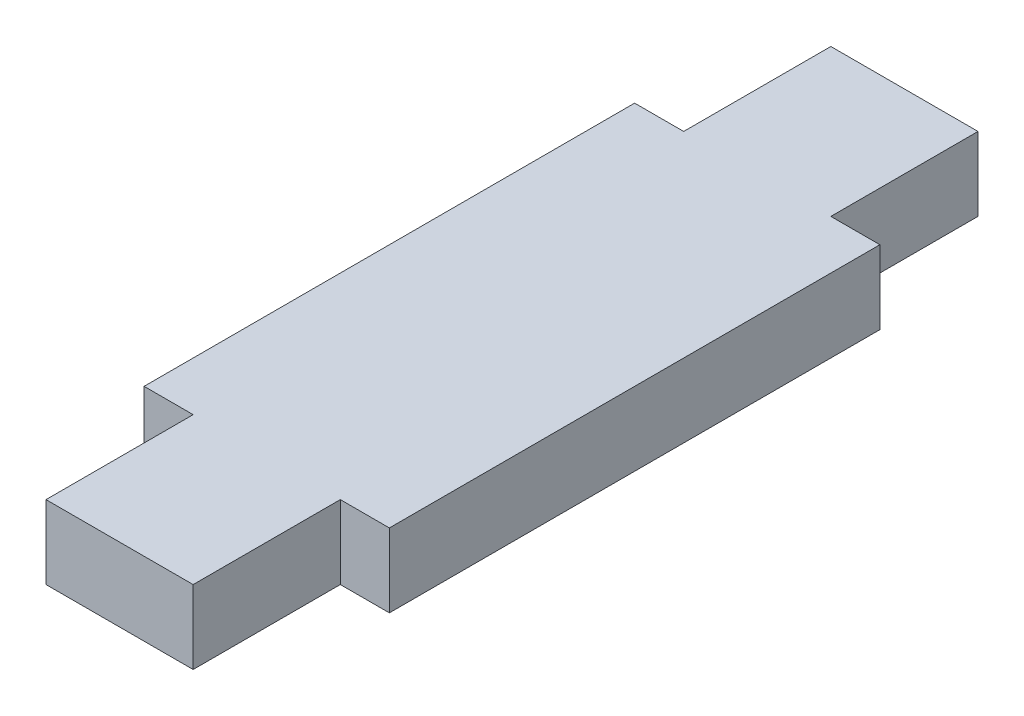
SolidWorks part; units mm, degrees
ref_plane "Front Plane" through (0, 0, 0) normal (0, 0, 1) x (1, 0, 0)
ref_plane "Top Plane" through (0, 0, 0) normal (0, 1, 0) x (1, 0, 0)
ref_plane "Right Plane" through (0, 0, 0) normal (1, 0, 0) x (0, 0, -1)
other "Configuration Table"
sketch "Sketch1" plane through (0, 0, 0) normal (0, 1, 0) x (1, 0, 0)
  line L0 (-5, 10) -> (-3, 10)
  line L2 (-5, 10) -> (-5, -10)
  line L4 (5, 10) -> (5, -10)
  line L5 (-5, 10) -> (5, -10) construction
  line L6 (-5, -10) -> (5, 10) construction
  line L12 (-3, 10) -> (-3, 16)
  line L17 (-3, 16) -> (3, 16)
  line L18 (3, 10) -> (3, 16)
  line L19 (3, 10) -> (5, 10)
  line L20 (-5, 0) -> (5, 0) construction
  line L21 (3, -10) -> (5, -10)
  line L22 (3, -10) -> (3, -16)
  line L23 (-3, -16) -> (3, -16)
  line L24 (-3, -10) -> (-3, -16)
  line L25 (-5, -10) -> (-3, -10)
  point P0 (0, 0)
  point P6 (0, -10)
  dimension "D1" = 20
  dimension "D2" = 10
  dimension "D3" = 6
  dimension "D4" = 6
extrude "Boss-Extrude1" add sketch "Sketch1" along normal blind 3
